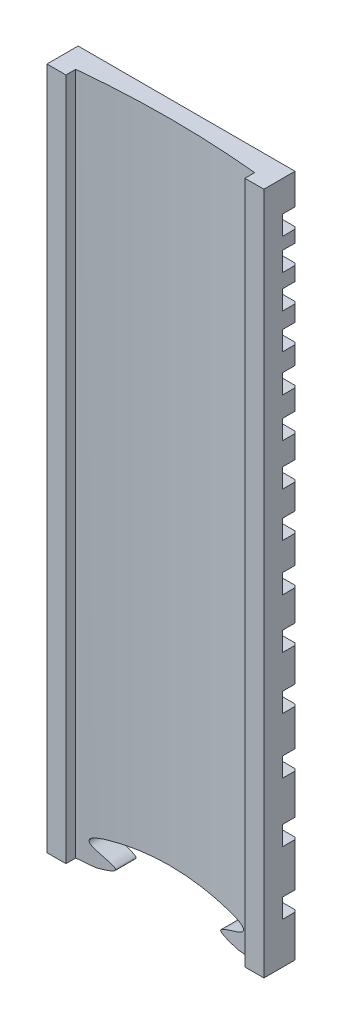
SolidWorks part; units mm, degrees
ref_plane "Front Plane" through (0, 0, 0) normal (0, 0, 1) x (1, 0, 0)
ref_plane "Top Plane" through (0, 0, 0) normal (0, 1, 0) x (1, 0, 0)
ref_plane "Right Plane" through (0, 0, 0) normal (1, 0, 0) x (0, 0, -1)
sketch "Sketch1" plane through (0, 0, 0) normal (0, 0, 1) x (1, 0, 0)
  line L0 (0, 464.91) -> (0, -53.7621) construction
  line L1 (207.2765, 0) -> (-181.268, 0) construction
  line L2 (23.8804, 464.91) -> (23.8804, -53.7621) construction
  line L3 (-23.8804, 464.91) -> (-23.8804, -53.7621) construction
  line L4 (16.5652, 464.91) -> (16.5652, -53.7621) construction
  line L5 (-16.5652, 464.91) -> (-16.5652, -53.7621) construction
  line L6 (-39.4637, 452.8091) -> (40.6786, 452.8091) construction
  line L7 (40.6786, 4) -> (-39.4637, 4) construction
  line L8 (-16.5652, 4) -> (-23.8804, 452.8091) construction
  line L9 (23.8804, 452.8091) -> (16.5652, 4) construction
  line L10 (-39.4637, 442.2134) -> (40.6786, 442.2134) construction
  line L11 (40.6786, 31.6398) -> (-39.4637, 31.6398) construction
  line L12 (40.6786, 430.9875) -> (-39.4637, 430.9875) construction
  line L13 (-39.4637, 455.3091) -> (40.6786, 455.3091)
  line L14 (-39.4637, 65.2793) -> (40.6786, 65.2793) construction
  line L15 (-39.4637, 364.0154) -> (40.6786, 364.0154) construction
  line L16 (-39.4637, 444.7134) -> (40.6786, 444.7134)
  line L17 (-39.4637, 61.2793) -> (40.6786, 61.2793)
  line L18 (-39.4637, 97.0308) -> (40.6786, 97.0308) construction
  line L19 (-39.4637, 93.0308) -> (40.6786, 93.0308)
  line L20 (40.6786, 127.0002) -> (-39.4637, 127.0002) construction
  line L21 (-39.4637, 67.7793) -> (40.6786, 67.7793)
  line L22 (-39.4637, 155.2875) -> (40.6786, 155.2875) construction
  line L23 (-39.4637, 366.5154) -> (40.6786, 366.5154)
  line L24 (40.6786, 181.9872) -> (-39.4637, 181.9872) construction
  line L25 (-39.4637, 99.5308) -> (40.6786, 99.5308)
  line L26 (-39.4637, 207.1884) -> (40.6786, 207.1884) construction
  line L27 (-39.4637, 151.2875) -> (40.6786, 151.2875)
  line L28 (40.6786, 230.9751) -> (-39.4637, 230.9751) construction
  line L29 (-39.4637, 157.7875) -> (40.6786, 157.7875)
  line L30 (-39.4637, 253.4267) -> (40.6786, 253.4267) construction
  line L31 (-39.4637, 203.1883) -> (40.6786, 203.1883)
  line L32 (40.6786, 274.6183) -> (-39.4637, 274.6183) construction
  line L33 (-39.4637, 209.6884) -> (40.6786, 209.6884)
  line L34 (-39.4637, 294.6205) -> (40.6786, 294.6205) construction
  line L35 (-39.4637, 249.4267) -> (40.6786, 249.4267)
  line L36 (40.6786, 313.5) -> (-39.4637, 313.5) construction
  line L37 (-39.4637, 255.9267) -> (40.6786, 255.9267)
  line L38 (-39.4637, 331.3199) -> (40.6786, 331.3199) construction
  line L39 (-39.4637, 290.6205) -> (40.6786, 290.6205)
  line L40 (40.6786, 348.1397) -> (-39.4637, 348.1397) construction
  line L41 (-39.4637, 297.1205) -> (40.6786, 297.1205)
  line L42 (-39.4637, 379.0001) -> (40.6786, 379.0001) construction
  line L43 (-39.4637, 327.3199) -> (40.6786, 327.3199)
  line L44 (40.6786, 393.1438) -> (-39.4637, 393.1437) construction
  line L45 (-39.4637, 333.8199) -> (40.6786, 333.8199)
  line L46 (-39.4637, 406.4936) -> (40.6786, 406.4936) construction
  line L47 (-39.4637, 360.0154) -> (40.6786, 360.0154)
  line L48 (40.6786, 419.0942) -> (-39.4637, 419.0942) construction
  line L49 (-39.4637, 381.5001) -> (40.6786, 381.5001)
  line L50 (-39.4637, 375.0001) -> (40.6786, 375.0001)
  line L51 (-39.4637, 408.9936) -> (40.6786, 408.9936)
  line L52 (-39.4637, 402.4936) -> (40.6786, 402.4936)
  line L53 (-39.4637, 438.2134) -> (40.6786, 438.2134)
  line L54 (-39.4637, 448.8091) -> (40.6786, 448.8091)
  line L55 (40.6786, 34.1398) -> (-39.4637, 34.1398)
  line L56 (40.6786, 433.4875) -> (-39.4637, 433.4875)
  line L57 (40.6786, 426.9875) -> (-39.4637, 426.9875)
  line L58 (40.6786, 415.0942) -> (-39.4637, 415.0942)
  line L59 (40.6786, 389.1438) -> (-39.4637, 389.1438)
  line L60 (40.6786, 129.5002) -> (-39.4637, 129.5002)
  line L61 (40.6786, 344.1397) -> (-39.4637, 344.1397)
  line L62 (40.6786, 184.4872) -> (-39.4637, 184.4872)
  line L63 (40.6786, 309.5) -> (-39.4637, 309.5)
  line L64 (40.6786, 233.4751) -> (-39.4637, 233.4751)
  line L65 (40.6786, 270.6183) -> (-39.4637, 270.6183)
  line L66 (40.6786, 277.1183) -> (-39.4637, 277.1183)
  line L67 (40.6786, 226.9751) -> (-39.4637, 226.9751)
  line L68 (40.6786, 316) -> (-39.4637, 316)
  line L69 (40.6786, 177.9872) -> (-39.4637, 177.9872)
  line L70 (40.6786, 350.6397) -> (-39.4637, 350.6397)
  line L71 (40.6786, 123.0002) -> (-39.4637, 123.0002)
  line L72 (40.6786, 395.6438) -> (-39.4637, 395.6438)
  line L73 (40.6786, 27.6398) -> (-39.4637, 27.6398)
  line L74 (40.6786, 421.5942) -> (-39.4637, 421.5942)
  line L75 (40.6786, 1.5) -> (-39.4637, 1.5)
  line L76 (40.6786, 8) -> (-39.4637, 8)
  line L77 (40.6786, 1.5) -> (40.6786, 8)
  line L78 (40.6786, 448.8091) -> (40.6786, 455.3091)
  line L79 (40.6786, 438.2134) -> (40.6786, 444.7134)
  line L80 (40.6786, 426.9875) -> (40.6786, 433.4875)
  line L81 (40.6786, 415.0942) -> (40.6786, 421.5942)
  line L82 (40.6786, 402.4936) -> (40.6786, 408.9936)
  line L83 (40.6786, 389.1438) -> (40.6786, 395.6438)
  line L84 (40.6786, 375.0001) -> (40.6786, 381.5001)
  line L85 (40.6786, 360.0154) -> (40.6786, 366.5154)
  line L86 (40.6786, 344.1397) -> (40.6786, 350.6397)
  line L87 (40.6786, 327.3199) -> (40.6786, 333.8199)
  line L88 (40.6786, 309.5) -> (40.6786, 316)
  line L89 (40.6786, 290.6205) -> (40.6786, 297.1205)
  line L90 (40.6786, 270.6183) -> (40.6786, 277.1183)
  line L91 (40.6786, 249.4267) -> (40.6786, 255.9267)
  line L92 (40.6786, 226.9751) -> (40.6786, 233.4751)
  line L93 (40.6786, 203.1883) -> (40.6786, 209.6884)
  line L94 (40.6786, 177.9872) -> (40.6786, 184.4872)
  line L95 (40.6786, 151.2875) -> (40.6786, 157.7875)
  line L96 (40.6786, 123.0002) -> (40.6786, 129.5002)
  line L97 (40.6786, 93.0308) -> (40.6786, 99.5308)
  line L98 (40.6786, 61.2793) -> (40.6786, 67.7793)
  line L99 (40.6786, 27.6398) -> (40.6786, 34.1398)
  line L100 (-39.4637, 1.5) -> (-39.4637, 8)
  line L101 (-39.4637, 448.8091) -> (-39.4637, 455.3091)
  line L102 (-39.4637, 438.2134) -> (-39.4637, 444.7134)
  line L103 (-39.4637, 426.9875) -> (-39.4637, 433.4875)
  line L104 (-39.4637, 415.0942) -> (-39.4637, 421.5942)
  line L105 (-39.4637, 402.4936) -> (-39.4637, 408.9936)
  line L106 (-39.4637, 389.1438) -> (-39.4637, 395.6438)
  line L107 (-39.4637, 375.0001) -> (-39.4637, 381.5001)
  line L108 (-39.4637, 360.0154) -> (-39.4637, 366.5154)
  line L109 (-39.4637, 344.1397) -> (-39.4637, 350.6397)
  line L110 (-39.4637, 327.3199) -> (-39.4637, 333.8199)
  line L111 (-39.4637, 309.5) -> (-39.4637, 316)
  line L112 (-39.4637, 290.6205) -> (-39.4637, 297.1205)
  line L113 (-39.4637, 270.6183) -> (-39.4637, 277.1183)
  line L114 (-39.4637, 249.4267) -> (-39.4637, 255.9267)
  line L115 (-39.4637, 226.9751) -> (-39.4637, 233.4751)
  line L116 (-39.4637, 203.1883) -> (-39.4637, 209.6884)
  line L117 (-39.4637, 177.9872) -> (-39.4637, 184.4872)
  line L118 (-39.4637, 151.2875) -> (-39.4637, 157.7875)
  line L119 (-39.4637, 123.0002) -> (-39.4637, 129.5002)
  line L120 (-39.4637, 93.0308) -> (-39.4637, 99.5308)
  line L121 (-39.4637, 61.2793) -> (-39.4637, 67.7793)
  line L122 (-39.4637, 27.6398) -> (-39.4637, 34.1398)
  dimension "D7" = 2.5
  dimension "D31" = 6.5
  dimension "D1" = 23.8804
  dimension "D2" = 23.8804
  dimension "D3" = 16.5652
  dimension "D4" = 16.5652
  dimension "D5" = 452.8091
  dimension "D6" = 4
  dimension "D9" = 6.5
  dimension "D10" = 31.6398
  dimension "D11" = 65.2793
  dimension "D12" = 97.0308
  dimension "D13" = 127.0002
  dimension "D14" = 155.2875
  dimension "D15" = 181.9872
  dimension "D16" = 207.1884
  dimension "D17" = 230.9751
  dimension "D18" = 253.4267
  dimension "D19" = 274.6183
  dimension "D20" = 294.6205
  dimension "D21" = 313.5
  dimension "D22" = 331.3199
  dimension "D23" = 348.1397
  dimension "D24" = 442.2134
  dimension "D25" = 430.9875
  dimension "D26" = 419.0942
  dimension "D27" = 406.4936
  dimension "D28" = 393.1438
  dimension "D29" = 379.0001
  dimension "D30" = 364.0154
  dimension "D33" = 6.5
  dimension "D8" = 2.5
  dimension "D32" = 2.5
sketch "Sketch2" plane through (0, 0, 0) normal (0, 0, 1) x (1, 0, 0)
  line L0 (30.163, 490.1178) -> (30.163, -68.1918) construction
  line L1 (-30.163, 490.1178) -> (-30.163, -68.1918) construction
  line L2 (0, 464.91) -> (0, -53.7621) construction
  line L3 (36.563, -68.1918) -> (36.563, 490.1178) construction
  line L4 (-36.563, 490.1178) -> (-36.563, -68.1918) construction
  line L5 (-36.563, 0) -> (36.563, 0)
  line L6 (207.2765, 0) -> (-181.268, 0) construction
  line L7 (36.563, 0) -> (36.563, 465.7035)
  line L8 (36.563, 465.7035) -> (-36.563, 465.7035)
  line L9 (-36.563, 465.7035) -> (-36.563, 0)
  dimension "D1" = 30.163
  dimension "D2" = 30.163
  dimension "D3" = 6.4
  dimension "D4" = 6.4
extrude "Boss-Extrude1" add sketch "Sketch2" along normal blind 12.8
sketch "Sketch3" plane through (0, 0, 0) normal (0, 1, 0) x (1, 0, 0)
  line L0 (38.7043, 0) -> (-38.1623, 0) construction
  line L1 (39.8582, -6.4) -> (-38.1623, -6.4) construction
  line L2 (-36.563, -12.8) -> (36.563, -12.8) construction
  line L3 (38.7043, -311.2) -> (0, -311.2) construction
  line L4 (30.163, -12.8) -> (30.163, -7.8961)
  line L5 (-30.163, -12.8) -> (-30.163, -7.8961)
  arc A0 (30.163, -7.8961) -> (-30.163, -7.8961) centre (0, -311.2) ccw
  dimension "D1" = 6.4
  dimension "D2" = 304.8
  dimension "D3" = 30.163
  dimension "D4" = 30.163
extrude "Cut-Extrude3" cut sketch "Sketch3" against normal through all and the other way through all flip side to cut
sketch "Sketch4" plane through (0, 0, 0) normal (0, 0, 1) x (1, 0, 0)
  line L1 (-36.563, 0) -> (36.563, 0)
  line L2 (-36.563, 0) -> (-36.563, -6.4)
  line L3 (-36.563, -6.4) -> (36.563, -6.4)
  line L4 (36.563, 0) -> (36.563, -6.4)
  dimension "D1" = 6.4
extrude "Boss-Extrude3" add sketch "Sketch4" along normal blind 12.8
ref_plane "Plane1" through (0, 0, 4) normal (0, 0, 1) x (1, 0, 0)
sketch "Sketch6" plane through (0, 0, 4) normal (0, 0, 1) x (1, 0, 0)
  line L4 (-23.9019, 235.1951) -> (-49.3974, 235.1951)
  line L26 (88.4047, 229.6) -> (-88.9547, 229.6) construction
  line L27 (-36.563, -6.4) -> (36.563, -6.4) construction
  line L28 (38.8194, 235.4451) -> (23.9282, 235.4451)
  line L29 (-23.9282, 235.4451) -> (-49.3974, 235.4451)
  line L36 (-43.0535, 233.9982) -> (-37.9136, 235.1951) construction
  line L37 (18.1118, 248.2421) -> (-43.0535, 248.2421) construction
  line L38 (38.8194, 235.1951) -> (23.9019, 235.1951)
  line L39 (0, 221.5497) -> (0, 263.5634) construction
  line L40 (38.8194, 234.9451) -> (23.8757, 234.9451)
  line L41 (-23.8757, 234.9451) -> (-49.3974, 234.9451)
  line L42 (38.8194, 235.4451) -> (38.8194, 471.8117)
  line L43 (38.8194, 471.8117) -> (-37.9136, 471.8117)
  line L44 (-37.9136, 471.8117) -> (-49.3974, 235.4451)
  spline S0 degree 2 poles (0, 247.3679) (-10.7842, 247.3592) (-21.1489, 244.7709) knots 0 0 0 1 1 1
  spline S1 degree 3 poles (-21.1489, 244.7709) (-37.3576, 240.3411) (-4.2165, 239.3715) (-23.9019, 235.1951) knots 0 0 0 0 1 1 1 1
  spline S2 degree 3 poles (21.1489, 244.7709) (37.3576, 240.3411) (4.2165, 239.3715) (23.9019, 235.1951) knots 0 0 0 0 1 1 1 1
  spline S3 degree 2 poles (0, 247.3679) (10.7842, 247.3592) (21.1489, 244.7709) knots 0 0 0 1 1 1
  spline S4 degree 1 poles (21.2121, 245.0128) (23.9282, 235.4451) knots 0 0 1 1 construction
  spline S5 degree 1 poles (0, 247.6179) (21.2121, 245.0128) knots 0 0 1 1 construction
  spline S6 degree 1 poles (0, 247.6179) (-21.2121, 245.0128) knots 0 0 1 1 construction
  spline S7 degree 1 poles (-21.2121, 245.0128) (-23.9282, 235.4451) knots 0 0 1 1 construction
  spline S8 degree 3 poles (23.9282, 235.4451) (23.6348, 235.5075) (23.0312, 235.6397) (21.9693, 235.8882) (20.8094, 236.1907) (19.6992, 236.5347) (18.5615, 236.9688) (17.9094, 237.3695) (17.6986, 237.6707) (17.6829, 237.7979) (17.739, 237.9582) (18.0148, 238.258) (18.7071, 238.6703) (19.903, 239.162) (21.7672, 239.8167) (23.7279, 240.4802) (25.2001, 241.2084) (25.8203, 241.7115) (26.0573, 242.2461) (25.9835, 242.8528) (25.4979, 243.3457) (24.6357, 243.835) (23.7639, 244.2108) (22.8283, 244.5374) (21.9574, 244.8043) (21.4557, 244.9462) (21.2121, 245.0128) knots -0.000055 -0.000055 -0.000055 -0.000055 0.015564 0.031183 0.062421 0.09366 0.124898 0.187374 0.218612 0.24985 0.281088 0.312326 0.374802 0.437278 0.499755 0.624707 0.687183 0.749659 0.780897 0.812135 0.874612 0.90585 0.937088 0.968326 0.983945 0.999564 0.999564 0.999564 0.999564
  spline S9 degree 2 poles (21.2121, 245.0128) (10.816, 247.6092) (0, 247.6179) knots -0.000009 -0.000009 -0.000009 1.000129 1.000129 1.000129
  spline S10 degree 2 poles (0, 247.6179) (-10.816, 247.6092) (-21.2121, 245.0128) knots -0.000009 -0.000009 -0.000009 1.000129 1.000129 1.000129
  spline S11 degree 3 poles (-21.2121, 245.0128) (-21.4557, 244.9462) (-21.9574, 244.8043) (-22.8283, 244.5374) (-23.7639, 244.2108) (-24.6357, 243.835) (-25.4979, 243.3457) (-25.9835, 242.8528) (-26.0573, 242.2461) (-25.8203, 241.7115) (-25.2001, 241.2084) (-23.7279, 240.4802) (-21.7672, 239.8167) (-19.903, 239.162) (-18.7071, 238.6703) (-18.0148, 238.258) (-17.739, 237.9582) (-17.6829, 237.7979) (-17.6986, 237.6707) (-17.9094, 237.3695) (-18.5615, 236.9688) (-19.6992, 236.5347) (-20.8094, 236.1907) (-21.9693, 235.8882) (-23.0312, 235.6397) (-23.6348, 235.5075) (-23.9282, 235.4451) knots -0.000055 -0.000055 -0.000055 -0.000055 0.015564 0.031183 0.062421 0.09366 0.124898 0.187374 0.218612 0.24985 0.312326 0.374802 0.499755 0.562231 0.624707 0.687183 0.718421 0.749659 0.780897 0.812135 0.874612 0.90585 0.937088 0.968326 0.983945 0.999564 0.999564 0.999564 0.999564
  spline S12 degree 1 poles (21.0857, 244.529) (23.8757, 234.9451) knots 0 0 1 1 construction
  spline S13 degree 1 poles (0, 247.1179) (21.0857, 244.529) knots 0 0 1 1 construction
  spline S14 degree 1 poles (0, 247.1179) (-21.0857, 244.529) knots 0 0 1 1 construction
  spline S15 degree 1 poles (-21.0857, 244.529) (-23.8757, 234.9451) knots 0 0 1 1 construction
  spline S16 degree 3 poles (23.8757, 234.9451) (23.5787, 235.0082) (22.9678, 235.1413) (21.8899, 235.3927) (20.708, 235.6996) (19.5654, 236.0516) (18.6696, 236.3915) (18.0001, 236.7235) (17.5327, 237.0576) (17.2381, 237.4209) (17.1559, 237.8621) (17.323, 238.2556) (17.723, 238.6714) (18.4869, 239.1197) (19.7184, 239.6272) (21.1286, 240.1222) (22.5715, 240.6172) (23.8953, 241.1217) (24.9459, 241.6374) (25.4407, 242.0735) (25.5382, 242.3329) (25.5244, 242.4959) (25.3759, 242.7409) (25.0138, 243.0449) (24.423, 243.3812) (23.5911, 243.7412) (22.6782, 244.0603) (21.822, 244.3229) (21.3261, 244.4633) (21.0857, 244.529) knots 0.000055 0.000055 0.000055 0.000055 0.015686 0.031317 0.062579 0.093841 0.125102 0.156364 0.187626 0.218888 0.25015 0.281412 0.312674 0.375197 0.437721 0.500245 0.562768 0.625292 0.687816 0.75034 0.781601 0.812863 0.844125 0.875387 0.906649 0.937911 0.969173 0.984804 1.000434 1.000434 1.000434 1.000434
  spline S17 degree 2 poles (21.0857, 244.529) (10.7523, 247.1092) (0, 247.1179) knots 0.000009 0.000009 0.000009 0.99987 0.99987 0.99987
  spline S18 degree 2 poles (0, 247.1179) (-10.7523, 247.1092) (-21.0857, 244.529) knots 0.000009 0.000009 0.000009 0.99987 0.99987 0.99987
  spline S19 degree 3 poles (-21.0857, 244.529) (-21.3261, 244.4633) (-21.822, 244.3229) (-22.6782, 244.0603) (-23.5911, 243.7412) (-24.423, 243.3812) (-25.0138, 243.0449) (-25.3759, 242.7409) (-25.5244, 242.4959) (-25.5382, 242.3329) (-25.4407, 242.0735) (-24.9459, 241.6374) (-23.8953, 241.1217) (-22.5715, 240.6172) (-21.1286, 240.1222) (-19.7184, 239.6272) (-18.4869, 239.1197) (-17.723, 238.6714) (-17.323, 238.2556) (-17.1559, 237.8621) (-17.2381, 237.4209) (-17.5327, 237.0576) (-18.0001, 236.7235) (-18.6696, 236.3915) (-19.5654, 236.0516) (-20.708, 235.6996) (-21.8899, 235.3927) (-22.9678, 235.1413) (-23.5787, 235.0082) (-23.8757, 234.9451) knots 0.000055 0.000055 0.000055 0.000055 0.015686 0.031317 0.062579 0.093841 0.125102 0.156364 0.187626 0.218888 0.25015 0.312674 0.375197 0.437721 0.500245 0.562768 0.625292 0.687816 0.719078 0.75034 0.781601 0.812863 0.844125 0.875387 0.906649 0.937911 0.969173 0.984804 1.000434 1.000434 1.000434 1.000434
  dimension "D1" = 236
  dimension "D2" = 0.25
  dimension "D3" = 0.25
chamfer "Chamfer5" distance 0.7 angle 45 4 edges at (0, 465.7035, 0) (-36.563, 229.6518, 0) (0, -6.4, 0) (36.563, 229.6518, 0)
extrude "Cut-Extrude4" cut sketch "Sketch1" along normal blind 5
ref_plane "Plane2" through (0, 0, 12.8) normal (0, 0, 1) x (1, 0, 0)
sketch "Sketch7" plane through (0, 0, 12.8) normal (0, 0, 1) x (1, 0, 0)
  line L1 (-36.563, 465.7035) -> (36.563, 465.7035)
  line L2 (-36.563, 465.7035) -> (-36.563, -6.4)
  line L3 (-36.563, -6.4) -> (36.563, -6.4)
  line L4 (36.563, 465.7035) -> (36.563, -6.4)
extrude "Cut-Extrude7" cut sketch "Sketch7" against normal blind 1.6
extrude "Cut-Extrude8" cut sketch "Sketch6" against normal blind 10 and the other way blind 10 flip side to cut contours L44 L29 S11 S10 S9 S8 L28 L42 L43
